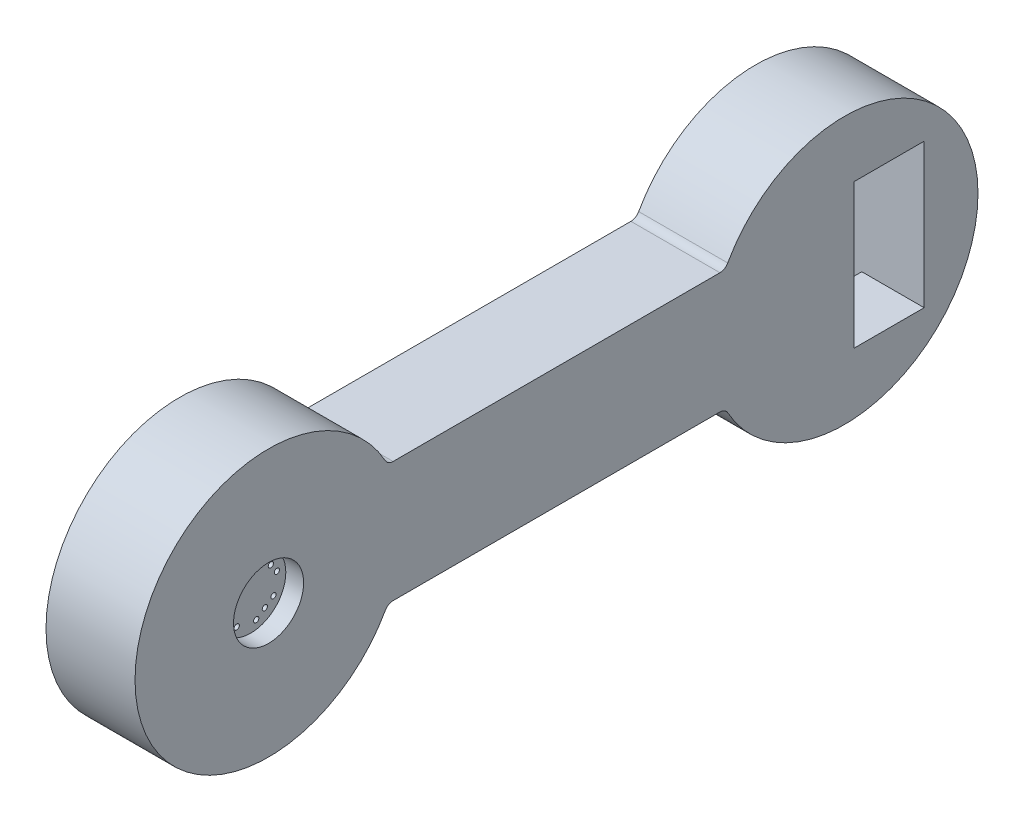
SolidWorks part; units mm, degrees
ref_plane "Front Plane" through (0, 0, 0) normal (0, 0, 1) x (1, 0, 0)
ref_plane "Top Plane" through (0, 0, 0) normal (0, 1, 0) x (1, 0, 0)
ref_plane "Right Plane" through (0, 0, 0) normal (1, 0, 0) x (0, 0, -1)
sketch "Sketch1" plane through (0, 0, 0) normal (1, 0, 0) x (0, 0, -1)
  line L0 (33.9978, 17.1976) -> (130.3019, 17.1976)
  line L1 (33.9978, -17.1976) -> (130.3019, -17.1976)
  arc A2 (33.9978, 17.1976) -> (33.9978, -17.1976) centre (0, 0) ccw
  arc A3 (130.3019, -17.1976) -> (130.3019, 17.1976) centre (164.2997, 0) ccw
  dimension "D2" = 38.1
  dimension "D1" = 102.262
extrude "Boss-Extrude1" add sketch "Sketch1" along normal blind 25.4
fillet "Fillet1" radius 2.54 4 edges at (12.7, 17.1976, -130.3019) (12.7, 17.1976, -33.9978) (12.7, -17.1976, -33.9978) (12.7, -17.1976, -130.3019)
sketch "Sketch2" plane through (25.4, 0, 0) normal (1, 0, 0) x (0, 0, -1)
  circle A0 centre (0, 0) radius 10
extrude "Cut-Extrude2" cut sketch "Sketch2" against normal blind 5.08
sketch "Sketch3" plane through (0, 0, 0) normal (-1, 0, 0) x (0, 0, 1)
  line L0 (-164.2997, 0) -> (-202.3997, 0) construction
  line L2 (-174.3327, 20.574) -> (-154.2667, 20.574)
  line L3 (-174.3327, 20.574) -> (-174.3327, -20.574)
  line L4 (-174.3327, -20.574) -> (-154.2667, -20.574)
  line L5 (-154.2667, 20.574) -> (-154.2667, -20.574)
  line L6 (-174.3327, 20.574) -> (-154.2667, -20.574) construction
  line L7 (-174.3327, -20.574) -> (-154.2667, 20.574) construction
  arc A0 (-130.9949, 18.504) -> (-130.9949, -18.504) centre (-164.2997, 0) ccw construction
  dimension "D1" = 20.066
  dimension "D2" = 41.148
extrude "Extrude-Thin1" [suppressed] add sketch "Sketch3" along normal blind 26.797 thin
sketch "Sketch6" plane through (25.4, 0, 0) normal (1, 0, 0) x (0, 0, -1)
  line L0 (202.3997, 0) -> (87.7937, 0) construction
  line L1 (166.9667, -20.574) -> (187.0327, -20.574)
  line L2 (166.9667, -20.574) -> (166.9667, 20.574)
  line L3 (166.9667, 20.574) -> (187.0327, 20.574)
  line L4 (187.0327, -20.574) -> (187.0327, 20.574)
  line L5 (166.9667, -20.574) -> (187.0327, 20.574) construction
  line L6 (166.9667, 20.574) -> (187.0327, -20.574) construction
  arc A0 (130.9949, -18.504) -> (130.9949, 18.504) centre (164.2997, 0) ccw construction
  point P0 (176.9997, 0)
  dimension "D1" = 20.066
  dimension "D2" = 41.148
  dimension "D3" = 25.4
extrude "Cut-Extrude3" cut sketch "Sketch6" against normal up to next
sketch "Sketch9" plane through (0, 0, 0) normal (-1, 0, 0) x (0, 0, 1)
  line L0 (-187.0327, -20.574) -> (-166.9667, -20.574)
  line L1 (-187.0327, -20.574) -> (-187.0327, -26.924)
  line L2 (-166.9667, -20.574) -> (-166.9667, -26.924)
  line L3 (-187.0327, -26.924) -> (-166.9667, -26.924)
  dimension "D1" = 6.35
extrude "Cut-Extrude6" cut sketch "Sketch9" against normal blind 7.62
fillet "Fillet2" radius 1.27 2 edges at (0, -26.924, -176.9997) (7.62, -26.924, -176.9997)
sketch "Sketch10" plane through (0, 0, 0) normal (-1, 0, 0) x (0, 0, 1)
  circle A0 centre (-4.0198, -5.7307) radius 0.75
  circle A1 centre (-6.4758, -4.0079) radius 0.75
  circle A2 centre (-1.5638, -7.4535) radius 0.75
  circle A3 centre (4.0079, -6.4758) radius 0.75
  circle A4 centre (5.7307, -4.0198) radius 0.75
  circle A5 centre (7.4535, -1.5638) radius 0.75
  circle A6 centre (6.4758, 4.0079) radius 0.75
  circle A7 centre (4.0198, 5.7307) radius 0.75
  circle A8 centre (1.5638, 7.4535) radius 0.75
  circle A9 centre (-4.0079, 6.4758) radius 0.75
  circle A10 centre (-5.7307, 4.0198) radius 0.75
  circle A11 centre (-7.4535, 1.5638) radius 0.75
extrude "Cut-Extrude7" cut sketch "Sketch10" against normal up to next
